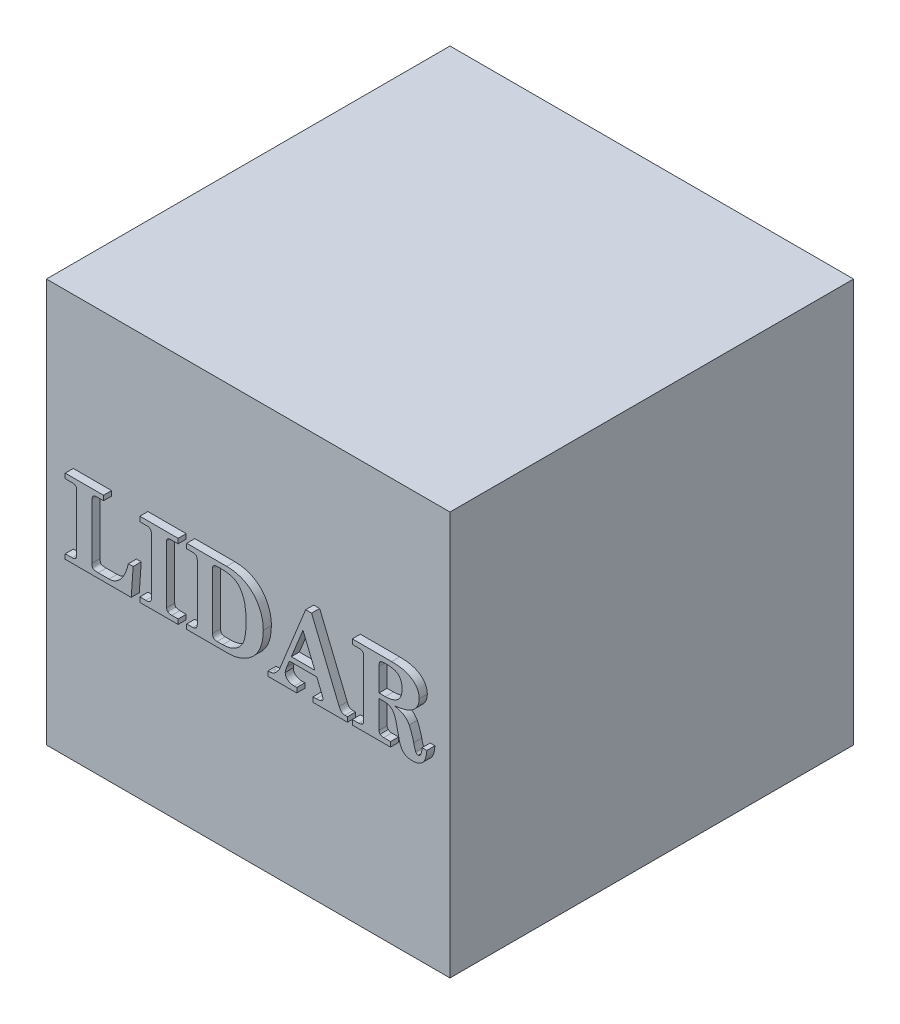
SolidWorks part; units mm, degrees
ref_plane "Front Plane" through (0, 0, 0) normal (0, 0, 1) x (1, 0, 0)
ref_plane "Top Plane" through (0, 0, 0) normal (0, 1, 0) x (1, 0, 0)
ref_plane "Right Plane" through (0, 0, 0) normal (1, 0, 0) x (0, 0, -1)
sketch "Sketch1" plane through (0, 0, 0) normal (0, 1, 0) x (1, 0, 0)
  line L1 (-25, 25) -> (25, 25)
  line L2 (-25, 25) -> (-25, -25)
  line L3 (-25, -25) -> (25, -25)
  line L4 (25, 25) -> (25, -25)
  line L5 (-25, 25) -> (25, -25) construction
  line L6 (-25, -25) -> (25, 25) construction
  point P0 (0, 0)
  dimension "D1" = 50
  dimension "D2" = 50
extrude "Boss-Extrude1" add sketch "Sketch1" along normal blind 50
sketch "Sketch2" plane through (0, 0, 25) normal (0, 0, 1) x (1, 0, 0)
  text T0 "<b>LIDAR</b>" font "@HYSWLongFangSong" height in points 36
extrude "Boss-Extrude2" add sketch "Sketch2" along normal blind 1
